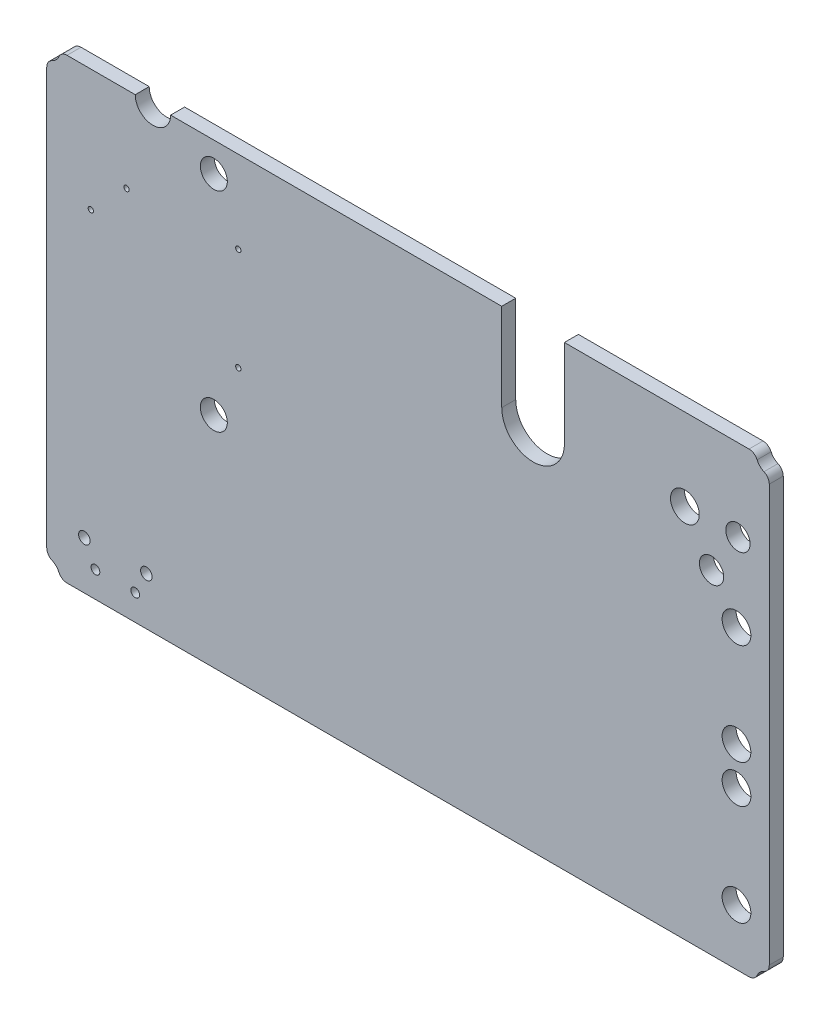
SolidWorks part; units mm, degrees
material "Copper"
ref_plane "top" through (0, 0, 0) normal (0, 0, 1) x (1, 0, 0)
ref_plane "front" through (0, 0, 0) normal (0, 1, 0) x (1, 0, 0)
ref_plane "right" through (0, 0, 0) normal (1, 0, 0) x (0, 0, -1)
sketch "Sketch1" plane through (0, 0, 0) normal (0, 0, 1) x (1, 0, 0)
  line L0 (45, 0) -> (35, 0) construction
  line L1 (-40.825, 25.825) -> (40.825, 25.825) construction
  line L2 (-40.825, 25.825) -> (-40.825, -25.825) construction
  line L3 (-40.825, -25.825) -> (40.825, -25.825) construction
  line L4 (40.825, 25.825) -> (40.825, -25.825) construction
  line L5 (-40.825, 25.825) -> (40.825, -25.825) construction
  line L6 (-40.825, -25.825) -> (40.825, 25.825) construction
  line L7 (45, -30) -> (-45, -30) construction
  line L8 (45, -30) -> (45, 30) construction
  line L9 (45, 30) -> (-45, 30) construction
  line L10 (-45, -30) -> (-45, 30) construction
  line L11 (45, -30) -> (-45, 30) construction
  line L12 (45, 30) -> (-45, -30) construction
  line L13 (35, -30) -> (35, 30) construction
  line L14 (-35, 30) -> (-35, -30) construction
  line L15 (-35, 0) -> (-45, 0) construction
  line L16 (36.25, -30) -> (36.25, 30) construction
  circle A0 centre (-40.825, 25.825) radius 1.5 construction
  circle A1 centre (40.825, 25.825) radius 1.5 construction
  circle A2 centre (40.825, -25.825) radius 1.5 construction
  circle A3 centre (-40.825, -25.825) radius 1.5 construction
  point P0 (0, 0)
  point P12 (0, 0)
  dimension "D3" = 3
  dimension "D1" = 51.65
  dimension "D2" = 81.65
  dimension "D4" = 60
  dimension "D5" = 90
  dimension "D6" = 10
  dimension "D7" = 10
  dimension "D8" = 8.75
sketch "Sketch3" plane through (0, 0, 0) normal (0, 0, 1) x (1, 0, 0)
  line L0 (-38.5337, -25.825) -> (38.5337, -25.825)
  line L1 (-40.825, -25.825) -> (40.825, -25.825) construction
  line L2 (40.825, -23.5337) -> (40.825, 23.5337)
  line L3 (40.825, 25.825) -> (40.825, -25.825) construction
  line L4 (38.5337, 25.825) -> (-38.5337, 25.825)
  line L5 (-40.825, 25.825) -> (40.825, 25.825) construction
  line L6 (-40.825, 23.5337) -> (-40.825, -23.5337)
  line L7 (-40.825, 25.825) -> (-40.825, -25.825) construction
  circle A0 centre (-40.825, -25.825) radius 1.5 construction
  circle A1 centre (40.825, -25.825) radius 1.5 construction
  circle A2 centre (40.825, 25.825) radius 1.5 construction
  circle A3 centre (-40.825, 25.825) radius 1.5 construction
  arc A4 (40.225, 24.4502) -> (39.4502, 25.225) centre (40.825, 25.825) cw
  arc A5 (40.225, -24.4502) -> (39.4502, -25.225) centre (40.825, -25.825) ccw
  arc A6 (-39.4502, -25.225) -> (-40.225, -24.4502) centre (-40.825, -25.825) ccw
  arc A7 (-40.225, 24.4502) -> (-39.4502, 25.225) centre (-40.825, 25.825) ccw
  arc A8 (-38.5337, 25.825) -> (-39.4502, 25.225) centre (-38.5337, 24.825) ccw
  arc A9 (-40.825, 23.5337) -> (-40.225, 24.4502) centre (-39.825, 23.5337) cw
  arc A10 (40.225, 24.4502) -> (40.825, 23.5337) centre (39.825, 23.5337) cw
  arc A11 (40.825, -23.5337) -> (40.225, -24.4502) centre (39.825, -23.5337) cw
  arc A12 (38.5337, -25.825) -> (39.4502, -25.225) centre (38.5337, -24.825) ccw
  arc A13 (-38.5337, -25.825) -> (-39.4502, -25.225) centre (-38.5337, -24.825) cw
  arc A14 (-40.825, -23.5337) -> (-40.225, -24.4502) centre (-39.825, -23.5337) ccw
  arc A15 (39.4502, 25.225) -> (38.5337, 25.825) centre (38.5337, 24.825) ccw
  point P30 (-39.325, 25.825)
  point P33 (-40.825, 24.325)
  point P40 (40.825, 24.325)
  point P43 (40.825, -24.325)
  point P46 (39.325, -25.825)
  point P49 (-39.325, -25.825)
  point P52 (-40.825, -24.325)
  point P55 (39.325, 25.825)
  dimension "D1" = 1
  dimension "D2" = 1
  dimension "D3" = 1
  dimension "D4" = 1
extrude "Boss-Extrude2" add sketch "Sketch3" along normal blind 1.58
sketch "Sketch5" plane through (0, 0, 0) normal (0, 0, -1) x (1, 0, 0)
  line L5 (-19.175, -16.525) -> (-19.175, -4.925) construction
  line L8 (-19.175, -10.725) -> (-17.675, -10.725) construction
  line L11 (40.825, -25.825) -> (32.475, -25.825) construction
  line L12 (38.5337, -25.825) -> (-38.5337, -25.825) construction
  line L13 (-19.175, -10.725) -> (-21.945, -10.725) construction
  line L14 (32.475, -25.825) -> (23.475, -25.825) construction
  line L15 (32.475, -25.825) -> (32.475, -11.425) construction
  line L16 (32.475, -11.425) -> (23.475, -11.425) construction
  line L17 (23.475, -25.825) -> (23.475, -11.425) construction
  line L19 (38.5337, -25.825) -> (-38.5337, -25.825) construction
  line L20 (-21.945, -22.525) -> (-21.945, 1.075) construction
  circle A11 centre (-19.175, -4.925) radius 0.3
  circle A12 centre (-19.175, -16.525) radius 0.3
  circle A13 centre (-21.945, -22.525) radius 1.525
  circle A14 centre (-21.945, 1.075) radius 1.525
  dimension "D4" = 0.6
  dimension "D5" = 60
  dimension "D6" = 3.05
  dimension "D7" = 3.05
  dimension "D2" = 11.6
  dimension "D3" = 15.1
  dimension "D8" = 23.6
  dimension "D9" = 2.77
  dimension "D10" = 1.5
  dimension "D11" = 8.35
  dimension "D12" = 9
  dimension "D13" = 14.4
sketch "Sketch6" plane through (0, 0, 1.58) normal (0, 0, 1) x (1, 0, 0)
  line L2 (-19.175, 16.525) -> (-19.175, 4.925) construction
  line L3 (-45, -30) -> (-45, 30) construction
  line L4 (45, -30) -> (-45, -30) construction
  line L5 (45, -30) -> (45, 30) construction
  line L6 (45, 30) -> (-45, 30) construction
  line L7 (40.825, 25.825) -> (40.825, -25.825) construction
  line L8 (-40.825, 25.825) -> (40.825, 25.825) construction
  line L9 (-40.825, -25.825) -> (40.825, -25.825) construction
  line L10 (-40.825, 25.825) -> (-40.825, -25.825) construction
  line L16 (45, 0) -> (35, 0) construction
  line L17 (35, -30) -> (35, 30) construction
  line L18 (-35, 0) -> (-45, 0) construction
  line L19 (-35, 30) -> (-35, -30) construction
  line L22 (-19.175, 16.525) -> (-19.175, 4.925) construction
  line L23 (-45, -30) -> (-45, 30) construction
  line L24 (45, -30) -> (-45, -30) construction
  line L25 (45, -30) -> (45, 30) construction
  line L26 (45, 30) -> (-45, 30) construction
  line L27 (40.825, 25.825) -> (40.825, -25.825) construction
  line L28 (-40.825, 25.825) -> (40.825, 25.825) construction
  line L29 (-40.825, -25.825) -> (40.825, -25.825) construction
  line L30 (-40.825, 25.825) -> (-40.825, -25.825) construction
  line L36 (45, 0) -> (35, 0) construction
  line L37 (35, -30) -> (35, 30) construction
  line L38 (-35, 0) -> (-45, 0) construction
  line L39 (-35, 30) -> (-35, -30) construction
  circle A1 centre (-19.175, 16.525) radius 0.3 construction
  circle A2 centre (-19.175, 4.925) radius 0.3 construction
  circle A4 centre (-40.825, -25.825) radius 1.5 construction
  circle A5 centre (40.825, -25.825) radius 1.5 construction
  circle A6 centre (40.825, 25.825) radius 1.5 construction
  circle A7 centre (-40.825, 25.825) radius 1.5 construction
  circle A16 centre (-19.175, 16.525) radius 0.3
  circle A17 centre (-19.175, 4.925) radius 0.3
  circle A19 centre (-40.825, -25.825) radius 1.5 construction
  circle A20 centre (40.825, -25.825) radius 1.5 construction
  circle A21 centre (40.825, 25.825) radius 1.5 construction
  circle A22 centre (-40.825, 25.825) radius 1.5 construction
  circle A30 centre (35, 0) radius 0.6048 construction
sketch "Sketch7" plane through (0, 0, 0) normal (0, 0, -1) x (1, 0, 0)
  line L0 (45, 30) -> (45, -30) construction
  line L1 (45, -30) -> (-45, -30) construction
  line L2 (45, 30) -> (-45, 30) construction
  line L3 (-45, 30) -> (-45, -30) construction
  line L4 (-38.5337, -25.825) -> (38.5337, -25.825)
  line L5 (40.825, -23.5337) -> (40.825, 23.5337)
  line L6 (38.5337, 25.825) -> (-38.5337, 25.825)
  line L7 (-40.825, 23.5337) -> (-40.825, -23.5337)
  line L8 (-38.5337, -25.825) -> (38.5337, -25.825) construction
  line L9 (40.825, -23.5337) -> (40.825, 23.5337) construction
  line L10 (38.5337, 25.825) -> (-38.5337, 25.825) construction
  line L11 (-40.825, 23.5337) -> (-40.825, -23.5337) construction
  line L12 (45, 30) -> (45, -30) construction
  line L13 (45, -30) -> (-45, -30) construction
  line L14 (45, 30) -> (-45, 30) construction
  line L15 (-45, 30) -> (-45, -30) construction
  line L16 (35, 30) -> (35, -30) construction
  line L17 (35, 30) -> (35, -30) construction
  line L18 (-36.5784, 20.4152) -> (-29.5684, 20.4152) construction
  line L19 (-30.8234, 22.9052) -> (-35.3234, 22.9052) construction
  line L20 (-33.0734, 20.4152) -> (-33.0734, 22.9052) construction
  line L21 (37.12, -7.675) -> (37.12, 3.755) construction
  circle A0 centre (-40.825, 25.825) radius 1.5 construction
  circle A1 centre (40.825, 25.825) radius 1.5 construction
  circle A2 centre (40.825, -25.825) radius 1.5 construction
  circle A3 centre (-40.825, -25.825) radius 1.5 construction
  circle A4 centre (-40.825, 25.825) radius 1.5 construction
  circle A5 centre (40.825, 25.825) radius 1.5 construction
  circle A6 centre (40.825, -25.825) radius 1.5 construction
  circle A7 centre (-40.825, -25.825) radius 1.5 construction
  circle A8 centre (-36.5784, 20.4152) radius 0.65
  circle A9 centre (-29.5684, 20.4152) radius 0.65
  circle A10 centre (-35.3234, 22.9052) radius 0.495
  circle A11 centre (-30.8234, 22.9052) radius 0.495
  arc A12 (-39.4502, -25.225) -> (-38.5337, -25.825) centre (-38.5337, -24.825) ccw
  arc A13 (38.5337, -25.825) -> (39.4502, -25.225) centre (38.5337, -24.825) ccw
  arc A14 (40.225, -24.4502) -> (39.4502, -25.225) centre (40.825, -25.825) ccw
  arc A15 (40.225, -24.4502) -> (40.825, -23.5337) centre (39.825, -23.5337) ccw
  arc A16 (40.825, 23.5337) -> (40.225, 24.4502) centre (39.825, 23.5337) ccw
  arc A17 (39.4502, 25.225) -> (40.225, 24.4502) centre (40.825, 25.825) ccw
  arc A18 (39.4502, 25.225) -> (38.5337, 25.825) centre (38.5337, 24.825) ccw
  arc A19 (-38.5337, 25.825) -> (-39.4502, 25.225) centre (-38.5337, 24.825) ccw
  arc A20 (-40.225, 24.4502) -> (-39.4502, 25.225) centre (-40.825, 25.825) ccw
  arc A21 (-40.225, 24.4502) -> (-40.825, 23.5337) centre (-39.825, 23.5337) ccw
  arc A22 (-40.825, -23.5337) -> (-40.225, -24.4502) centre (-39.825, -23.5337) ccw
  arc A23 (-39.4502, -25.225) -> (-40.225, -24.4502) centre (-40.825, -25.825) ccw
  arc A24 (-39.4502, -25.225) -> (-38.5337, -25.825) centre (-38.5337, -24.825) ccw construction
  arc A25 (38.5337, -25.825) -> (39.4502, -25.225) centre (38.5337, -24.825) ccw construction
  arc A26 (40.225, -24.4502) -> (39.4502, -25.225) centre (40.825, -25.825) ccw construction
  arc A27 (40.225, -24.4502) -> (40.825, -23.5337) centre (39.825, -23.5337) ccw construction
  arc A28 (40.825, 23.5337) -> (40.225, 24.4502) centre (39.825, 23.5337) ccw construction
  arc A29 (39.4502, 25.225) -> (40.225, 24.4502) centre (40.825, 25.825) ccw construction
  arc A30 (39.4502, 25.225) -> (38.5337, 25.825) centre (38.5337, 24.825) ccw construction
  arc A31 (-38.5337, 25.825) -> (-39.4502, 25.225) centre (-38.5337, 24.825) ccw construction
  arc A32 (-40.225, 24.4502) -> (-39.4502, 25.225) centre (-40.825, 25.825) ccw construction
  arc A33 (-40.225, 24.4502) -> (-40.825, 23.5337) centre (-39.825, 23.5337) ccw construction
  arc A34 (-40.825, -23.5337) -> (-40.225, -24.4502) centre (-39.825, -23.5337) ccw construction
  arc A35 (-39.4502, -25.225) -> (-40.225, -24.4502) centre (-40.825, -25.825) ccw construction
  circle A36 centre (-35.8399, -12.06) radius 0.3
  circle A37 centre (-31.8101, -16.158) radius 0.3
  circle A38 centre (31.2864, -16.58) radius 1.625
  circle A39 centre (37.2835, -16.58) radius 1.375
  circle A40 centre (34.3, -11.8576) radius 1.375
  circle A41 centre (37.12, -7.675) radius 1.625
  circle A42 centre (37.12, 3.755) radius 1.625
  circle A43 centre (37.12, 8.065) radius 1.625
  circle A44 centre (37.12, 19.495) radius 1.625
  dimension "D2" = 1.3
  dimension "D3" = 1.3
  dimension "D4" = 0.99
  dimension "D5" = 0.99
  dimension "D11" = 0.6
  dimension "D12" = 0.6
  dimension "D13" = 3.25
  dimension "D14" = 2.75
  dimension "D15" = 2.75
  dimension "D16" = 3.25
  dimension "D17" = 3.25
  dimension "D18" = 3.25
  dimension "D19" = 3.25
  dimension "D6" = 4.5
  dimension "D7" = 7.01
  dimension "D8" = 2.49
  dimension "D9" = 2.9198
  dimension "D10" = 7.7516
  dimension "D1" = 0
sketch "Sketch8" plane through (0, 0, 1.58) normal (0, 0, 1) x (1, 0, 0)
  line L0 (10.5926, 15.9051) -> (10.5926, 25.825)
  line L1 (38.5337, 25.825) -> (-38.5337, 25.825) construction
  line L2 (17.6755, 15.9051) -> (17.6755, 25.825)
  circle A1 centre (14.134, 15.9051) radius 1.75
  circle A2 centre (14.134, 15.9051) radius 3.5415 construction
  arc A3 (10.5926, 15.9051) -> (17.6755, 15.9051) centre (14.134, 15.9051) ccw
extrude "Cut-Extrude4" cut sketch "Sketch8" against normal through all contours L0 A3 L2
extrude "Cut-Extrude9" cut sketch "Sketch6" against normal through all contours A16 | A17
extrude "Cut-Extrude10" cut sketch "Sketch5" against normal through all
extrude "Cut-Extrude11" cut sketch "Sketch7" against normal through all
sketch "Sketch13" plane through (0, 0, 1.58) normal (0, 0, 1) x (1, 0, 0)
  line L2 (10.5926, 25.825) -> (-38.5337, 25.825) construction
  line L3 (-40.825, 23.5337) -> (-40.825, -23.5337) construction
  circle A0 centre (-28.825, 25.825) radius 2
  dimension "D1" = 4
  dimension "D2" = 12
extrude "Cut-Extrude12" cut sketch "Sketch13" against normal through all
sketch "Brainboard Location" plane through (0, 0, 1.58) normal (0, 0, 1) x (1, 0, 0)
  line L0 (-19.175, 16.525) -> (-19.175, 4.925) construction
  line L1 (-19.175, 10.725) -> (-17.675, 10.725) construction
  dimension "D1" = 1.5
sketch "Sketch16" plane through (0, 0, 0) normal (0, 0, -1) x (-1, 0, 0)
  line L0 (40.825, 0) -> (-40.825, 0) construction
  line L1 (40.825, 23.5337) -> (40.825, -23.5337) construction
  line L2 (0, -25.825) -> (0, 25.825) construction
  line L3 (38.5337, -25.825) -> (-38.5337, -25.825) construction
  line L4 (-10.5926, 25.825) -> (26.825, 25.825) construction
  line L5 (-40.825, -23.5337) -> (-40.825, 23.5337) construction
sketch "Sketch17" plane through (0, 0, 1.58) normal (0, 0, 1) x (1, 0, 0)
  line L0 (0, 25.825) -> (0, -25.825) construction
  line L1 (-38.5337, -25.825) -> (38.5337, -25.825) construction
  line L2 (40.825, 0) -> (-40.825, 0) construction
  line L3 (40.825, -23.5337) -> (40.825, 23.5337) construction
sketch "ScreenConnectorPoint" plane through (0, 0, 1.58) normal (0, 0, 1) x (1, 0, 0)
  line L0 (0, -25.825) -> (0, 25.825) construction
  line L1 (-40.825, 0) -> (40.825, 0) construction
  point P0 (3.23, -16.43)
  dimension "D1" = 3.23
  dimension "D2" = 16.43
sketch "Sketch18" plane through (0, 0, 1.58) normal (0, 0, 1) x (1, 0, 0)
  line L1 (0, 0) -> (3.24, 0) construction
  line L2 (0, 0) -> (0, 0.19) construction
  line L3 (0, 0.19) -> (3.24, 0.19) construction
  line L4 (3.24, 0) -> (3.24, 0.19) construction
  dimension "D1" = 0.19
  dimension "D2" = 3.24
sketch3d "3DSketch1"
  line L0 (3.24, 0.19, 1.58) -> (3.24, 0.19, 24.6688) construction
equation "\"D3@Sketch7\"=\"D2@Sketch7\""
equation "\"D5@Sketch7\"=\"D4@Sketch7\""
equation "\"D15@Sketch7\"=\"D14@Sketch7\""
equation "\"D17@Sketch7\"=\"D16@Sketch7\""
equation "\"D18@Sketch7\"=\"D16@Sketch7\""
equation "\"D19@Sketch7\"=\"D16@Sketch7\""
